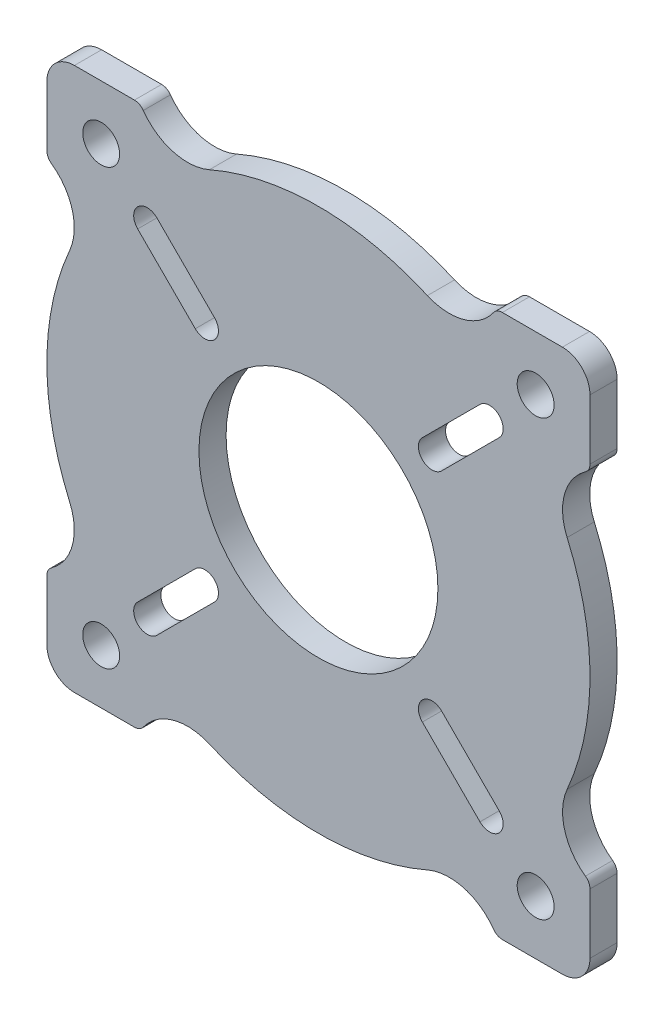
SolidWorks part; units mm, degrees
ref_plane "Plan de face" through (0, 0, 0) normal (0, 0, 1) x (1, 0, 0)
ref_plane "Plan de dessus" through (0, 0, 0) normal (0, 1, 0) x (1, 0, 0)
ref_plane "Plan de droite" through (0, 0, 0) normal (1, 0, 0) x (0, 0, -1)
sketch "Esquisse1" plane through (0, 0, 0) normal (0, 0, 1) x (1, 0, 0)
  line L0 (29.747, -33.2825) -> (19.1403, -22.6759)
  line L1 (22.6759, -19.1403) -> (33.2825, -29.747)
  line L2 (50, -44.9195) -> (50, -33.8621)
  line L3 (33.8724, -50) -> (44.9195, -50)
  line L4 (0, 0) -> (40, -40) construction
  line L5 (-33.2825, -29.747) -> (-22.6759, -19.1403)
  line L6 (33.2825, 29.747) -> (22.6759, 19.1403)
  line L7 (19.1403, 22.6759) -> (29.747, 33.2825)
  line L8 (44.9195, 50) -> (33.8621, 50)
  line L9 (-19.1403, -22.6759) -> (-29.747, -33.2825)
  line L10 (-44.9195, -50) -> (-33.8621, -50)
  line L11 (-50, -33.8724) -> (-50, -44.9195)
  line L12 (0, 0) -> (-40, -40) construction
  line L13 (-29.747, 33.2825) -> (-19.1403, 22.6759)
  line L14 (-22.6759, 19.1403) -> (-33.2825, 29.747)
  line L15 (50, 33.8724) -> (50, 44.9195)
  line L16 (0, 0) -> (40, 40) construction
  line L17 (0, 0) -> (0, 50) construction
  line L18 (0, 0) -> (50, 0) construction
  line L19 (-50, 44.9195) -> (-50, 33.8621)
  line L20 (-33.8724, 50) -> (-44.9195, 50)
  line L21 (0, 0) -> (-40, 40) construction
  circle A0 centre (0, 0) radius 10.5 construction
  arc A1 (45.7956, -20.0691) -> (50, 0) centre (0, 0) ccw
  arc A2 (45.7956, -20.0691) -> (49.1591, -32.2322) centre (54.9547, -24.0829) ccw
  arc A3 (20.0691, 45.7956) -> (0, 50) centre (0, 0) ccw
  arc A4 (20.0691, 45.7956) -> (32.2322, 49.1591) centre (24.0829, 54.9547) ccw
  arc A5 (33.8621, 50) -> (32.2322, 49.1591) centre (33.8621, 48) ccw
  arc A6 (50, 44.9195) -> (44.9195, 50) centre (44.9195, 44.9195) ccw
  arc A7 (49.1585, 32.2421) -> (45.7927, 20.0756) centre (54.9512, 24.0907) ccw
  arc A8 (49.1585, 32.2421) -> (50, 33.8724) centre (48, 33.8724) ccw
  arc A9 (50, 0) -> (45.7927, 20.0756) centre (0, 0) ccw
  arc A10 (50, -33.8621) -> (49.1591, -32.2322) centre (48, -33.8621) ccw
  arc A11 (44.9195, -50) -> (50, -44.9195) centre (44.9195, -44.9195) ccw
  arc A12 (32.2421, -49.1585) -> (20.0756, -45.7927) centre (24.0907, -54.9512) ccw
  arc A13 (32.2421, -49.1585) -> (33.8724, -50) centre (33.8724, -48) ccw
  arc A14 (0, -50) -> (20.0756, -45.7927) centre (0, 0) ccw
  arc A15 (29.747, -33.2825) -> (33.2825, -29.747) centre (31.5147, -31.5147) ccw
  arc A16 (22.6759, -19.1403) -> (19.1403, -22.6759) centre (20.9081, -20.9081) ccw
  circle A17 centre (40, -40) radius 3.4
  arc A18 (-20.0691, -45.7956) -> (0, -50) centre (0, 0) ccw
  arc A19 (-20.0691, -45.7956) -> (-32.2322, -49.1591) centre (-24.0829, -54.9547) ccw
  arc A20 (-33.8621, -50) -> (-32.2322, -49.1591) centre (-33.8621, -48) ccw
  arc A21 (-50, -44.9195) -> (-44.9195, -50) centre (-44.9195, -44.9195) ccw
  arc A22 (-49.1585, -32.2421) -> (-45.7927, -20.0756) centre (-54.9512, -24.0907) ccw
  arc A23 (-49.1585, -32.2421) -> (-50, -33.8724) centre (-48, -33.8724) ccw
  arc A24 (-50, 0) -> (-45.7927, -20.0756) centre (0, 0) ccw
  arc A25 (-33.2825, -29.747) -> (-29.747, -33.2825) centre (-31.5147, -31.5147) ccw
  arc A26 (-19.1403, -22.6759) -> (-22.6759, -19.1403) centre (-20.9081, -20.9081) ccw
  circle A27 centre (-40, -40) radius 3.4
  arc A28 (-45.7956, 20.0691) -> (-50, 0) centre (0, 0) ccw
  arc A29 (-45.7956, 20.0691) -> (-49.1591, 32.2322) centre (-54.9547, 24.0829) ccw
  arc A30 (-50, 33.8621) -> (-49.1591, 32.2322) centre (-48, 33.8621) ccw
  arc A31 (33.2825, 29.747) -> (29.747, 33.2825) centre (31.5147, 31.5147) ccw
  arc A32 (19.1403, 22.6759) -> (22.6759, 19.1403) centre (20.9081, 20.9081) ccw
  circle A33 centre (0, 0) radius 22
  arc A34 (-44.9195, 50) -> (-50, 44.9195) centre (-44.9195, 44.9195) ccw
  arc A35 (-32.2421, 49.1585) -> (-20.0756, 45.7927) centre (-24.0907, 54.9512) ccw
  arc A36 (-32.2421, 49.1585) -> (-33.8724, 50) centre (-33.8724, 48) ccw
  circle A37 centre (40, 40) radius 3.4
  arc A38 (0, 50) -> (-20.0756, 45.7927) centre (0, 0) ccw
  arc A39 (-29.747, 33.2825) -> (-33.2825, 29.747) centre (-31.5147, 31.5147) ccw
  circle A40 centre (0, 0) radius 14.5 construction
  arc A41 (-22.6759, 19.1403) -> (-19.1403, 22.6759) centre (-20.9081, 20.9081) ccw
  circle A42 centre (-40, 40) radius 3.4
  point P97 (0, 0)
  point P102 (0, 0)
  dimension "D1" = 2.5
  dimension "D2" = 29.5685
  dimension "D3" = 40
  dimension "D5" = 50
  dimension "D6" = 50
  dimension "D7" = 4
  dimension "D9" = 29
  dimension "D13" = 10
  dimension "D10" = 21
  dimension "D11" = 50
  dimension "D14" = 10
  dimension "D15" = 44
  dimension "D4" = 40
  dimension "D8" = 15
extrude "Boss.-Extru.2" add sketch "Esquisse1" along normal blind 5
